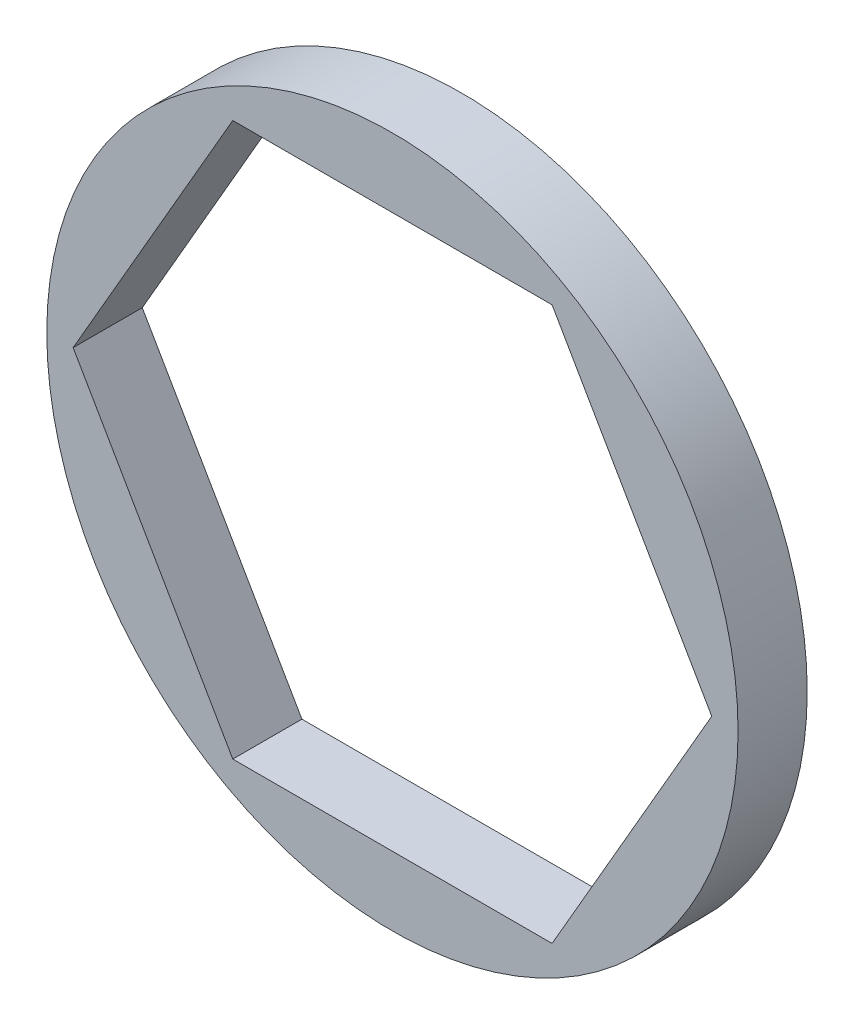
SolidWorks part; units mm, degrees
material "ABS"
ref_plane "Front Plane" through (0, 0, 0) normal (0, 0, 1) x (1, 0, 0)
ref_plane "Top Plane" through (0, 0, 0) normal (0, 1, 0) x (1, 0, 0)
ref_plane "Right Plane" through (0, 0, 0) normal (1, 0, 0) x (0, 0, -1)
sketch "Sketch1" plane through (0, 0, 0) normal (0, 0, 1) x (1, 0, 0)
  line L1 (-3.6662, -6.35) -> (3.6662, -6.35)
  line L2 (3.6662, -6.35) -> (7.3323, 0)
  line L3 (7.3323, 0) -> (3.6662, 6.35)
  line L4 (3.6662, 6.35) -> (-3.6662, 6.35)
  line L5 (-3.6662, 6.35) -> (-7.3323, 0)
  line L6 (-7.3323, 0) -> (-3.6662, -6.35)
  circle A0 centre (0, 0) radius 6.35 construction
  circle A1 centre (0, 0) radius 7.9375
  dimension "D1" = 12.7
  dimension "D2" = 15.875
extrude "Boss-Extrude1" add sketch "Sketch1" along normal blind 1.5875
